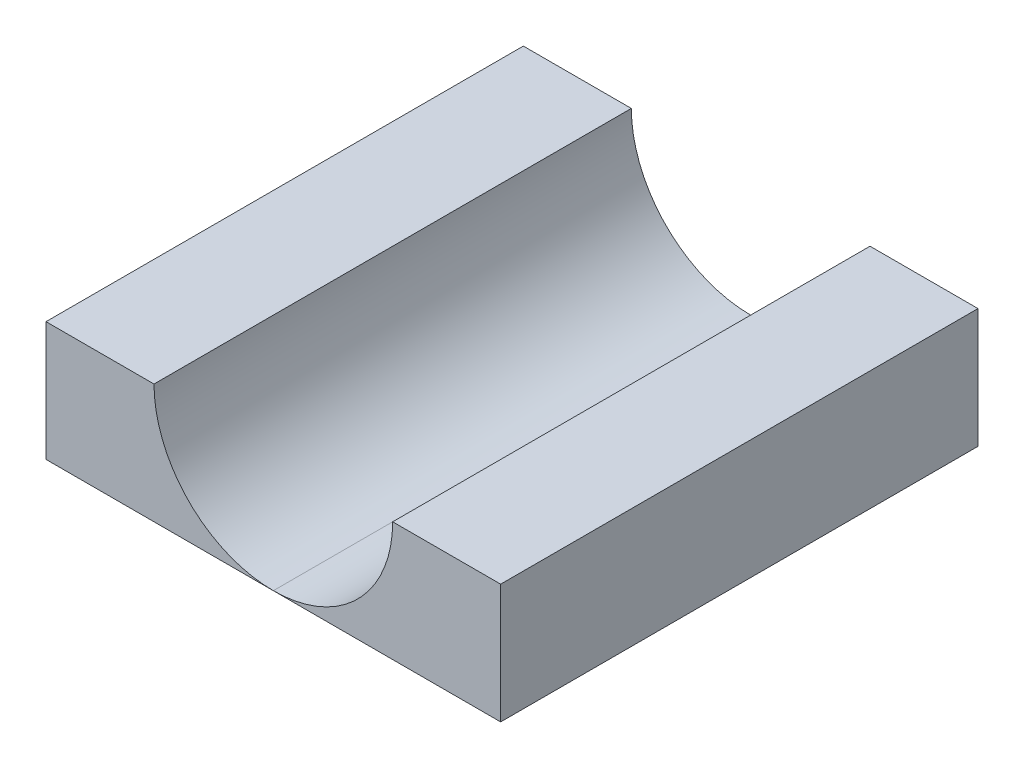
SolidWorks part; units mm, degrees
ref_plane "Front Plane" through (0, 0, 0) normal (0, 0, 1) x (1, 0, 0)
ref_plane "Top Plane" through (0, 0, 0) normal (0, 1, 0) x (1, 0, 0)
ref_plane "Right Plane" through (0, 0, 0) normal (1, 0, 0) x (0, 0, -1)
sketch "Sketch1" plane through (0, 0, 0) normal (0, 0, 1) x (1, 0, 0)
  line L0 (0, 0) -> (19.05, 0)
  line L1 (19.05, 0) -> (19.05, 5)
  line L2 (19.05, 5) -> (14.525, 5)
  line L3 (0, 5) -> (0, 0)
  line L4 (9.525, 5) -> (9.525, 0) construction
  line L5 (4.525, 5) -> (0, 5)
  arc A0 (4.525, 5) -> (14.525, 5) centre (9.525, 5) ccw
  point P7 (9.525, 0)
  point P8 (11.0883, 7.5)
  dimension "D1" = 10
  dimension "D2" = 19.05
extrude "Boss-Extrude1" add sketch "Sketch1" along normal blind 20 contours A0 L5 L3 L0 | A0 L0 L1 L2
